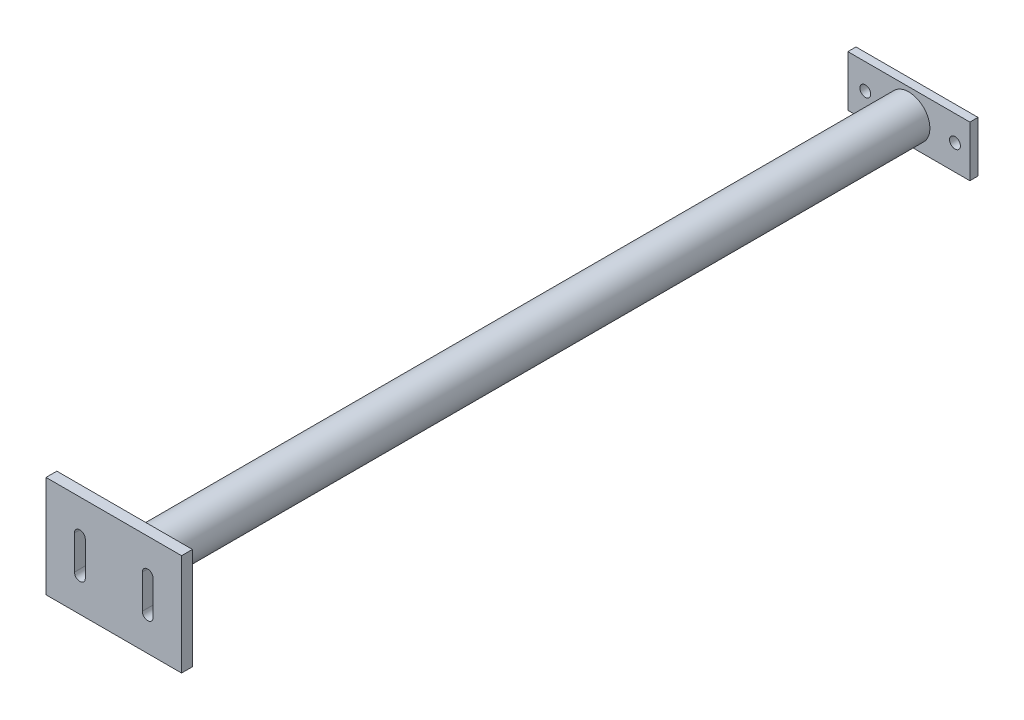
SolidWorks part; units mm, degrees
ref_plane "Front Plane" through (0, 0, 0) normal (0, 0, 1) x (1, 0, 0)
ref_plane "Top Plane" through (0, 0, 0) normal (0, 1, 0) x (1, 0, 0)
ref_plane "Right Plane" through (0, 0, 0) normal (1, 0, 0) x (0, 0, -1)
sketch "Sketch1" plane through (0, 0, 0) normal (0, 0, 1) x (1, 0, 0)
  circle A0 centre (0, 0) radius 31
  circle A1 centre (0, 0) radius 25
  dimension "D1" = 50
  dimension "D2" = 62
extrude "Boss-Extrude1" add sketch "Sketch1" along normal blind 1157
sketch "Sketch2" plane through (0, 0, 0) normal (0, 0, -1) x (-1, 0, 0)
  line L1 (-90, 37.5) -> (90, 37.5)
  line L2 (-90, 37.5) -> (-90, -37.5)
  line L3 (-90, -37.5) -> (90, -37.5)
  line L4 (90, 37.5) -> (90, -37.5)
  circle A0 centre (64.2276, 0) radius 8
  circle A1 centre (-68.0305, 0) radius 8
  dimension "D5" = 16
  dimension "D6" = 16
  dimension "D1" = 180
  dimension "D2" = 75
  dimension "D3" = 90
  dimension "D4" = 37.5
extrude "Boss-Extrude2" add sketch "Sketch2" along normal blind 12
sketch "Sketch3" plane through (0, 0, 1157) normal (0, 0, 1) x (1, 0, 0)
  line L0 (-50, 25) -> (-50, -25) construction
  line L1 (-100, 75) -> (100, 75)
  line L2 (-100, 75) -> (-100, -75)
  line L3 (-100, -75) -> (100, -75)
  line L4 (100, 75) -> (100, -75)
  line L7 (-42, 25) -> (-42, -25)
  line L8 (-120.6872, 0) -> (109.8433, 0) construction
  line L9 (-58, 25) -> (-58, -25)
  line L10 (0, 65.5765) -> (0, -62.7375) construction
  line L11 (50, 25) -> (50, -25) construction
  line L12 (42, 25) -> (42, -25)
  line L13 (58, 25) -> (58, -25)
  arc A2 (-42, 25) -> (-58, 25) centre (-50, 25) ccw
  arc A3 (-58, -25) -> (-42, -25) centre (-50, -25) ccw
  arc A4 (42, 25) -> (58, 25) centre (50, 25) cw
  arc A5 (58, -25) -> (42, -25) centre (50, -25) cw
  point P7 (-50, 0)
  point P18 (50, 0)
  dimension "D1" = 150
  dimension "D2" = 200
  dimension "D3" = 100
  dimension "D4" = 75
  dimension "D5" = 50
  dimension "D6" = 16
  dimension "D7" = 50
  dimension "D8" = 50
extrude "Boss-Extrude3" add sketch "Sketch3" along normal blind 16
